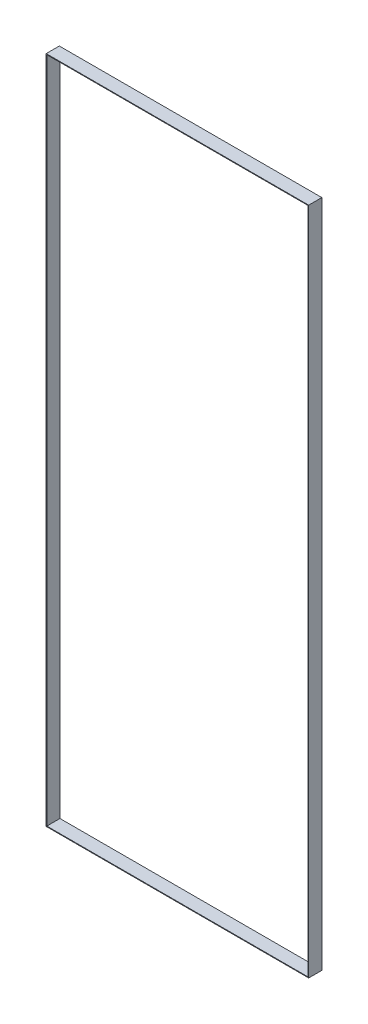
SolidWorks part; units mm, degrees
ref_plane "Front Plane" through (0, 0, 0) normal (0, 0, 1) x (1, 0, 0)
ref_plane "Top Plane" through (0, 0, 0) normal (0, 1, 0) x (1, 0, 0)
ref_plane "Right Plane" through (0, 0, 0) normal (1, 0, 0) x (0, 0, -1)
sketch "Sketch3" plane through (0, 0, 0) normal (0, 0, 1) x (1, 0, 0)
  line L1 (200, -510) -> (-200, -510)
  line L2 (200, -510) -> (200, 510)
  line L3 (200, 510) -> (-200, 510)
  line L4 (-200, -510) -> (-200, 510)
  line L5 (200, -510) -> (-200, 510) construction
  line L6 (200, 510) -> (-200, -510) construction
  point P0 (0, 0)
  dimension "D1" = 1020
  dimension "D2" = 400
extrude "Boss-Extrude1" add sketch "Sketch3" along normal blind 20
sketch "Sketch4" plane through (0, 0, 20) normal (0, 0, 1) x (1, 0, 0)
  line L1 (199, -509) -> (-199, -509)
  line L2 (199, -509) -> (199, 509)
  line L3 (199, 509) -> (-199, 509)
  line L4 (-199, -509) -> (-199, 509)
  line L5 (199, -509) -> (-199, 509) construction
  line L6 (199, 509) -> (-199, -509) construction
  point P0 (0, 0)
  dimension "D1" = 1018
  dimension "D2" = 398
extrude "Cut-Extrude1" cut sketch "Sketch4" against normal blind 20
